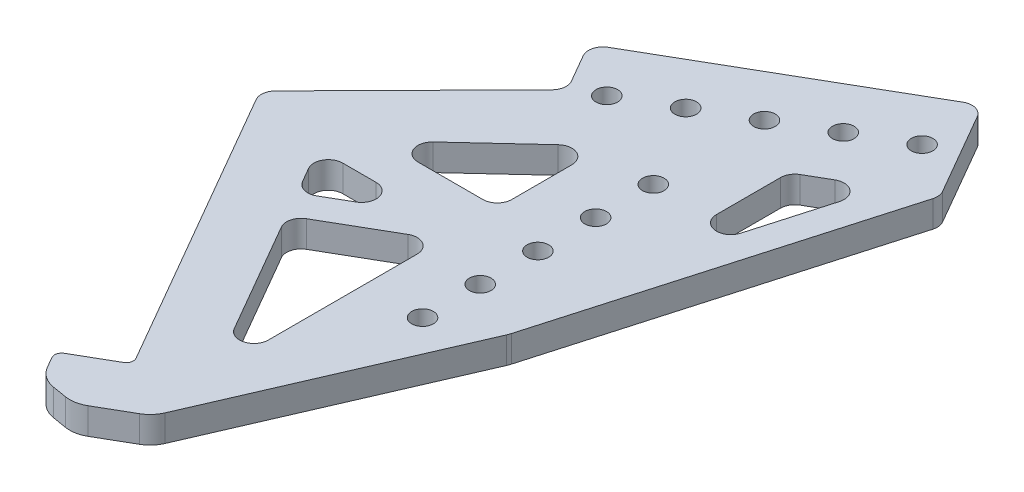
SolidWorks part; units mm, degrees
ref_plane "Front Plane" through (0, 0, 0) normal (0, 0, 1) x (1, 0, 0)
ref_plane "Top Plane" through (0, 0, 0) normal (0, 1, 0) x (1, 0, 0)
ref_plane "Right Plane" through (0, 0, 0) normal (1, 0, 0) x (0, 0, -1)
sketch "Sketch1" plane through (0, 0, 0) normal (0, 1, 0) x (1, 0, 0)
  line L0 (0, 0) -> (0, -101.6) construction
  line L1 (27.4963, 15.875) -> (-27.4963, -15.875) construction
  line L2 (25.9313, 0.3067) -> (12.7, -7.3323)
  line L3 (-11.0124, -123.6756) -> (12.6999, -68.9194)
  line L4 (-27.4963, -15.875) -> (-61.0935, -49.937)
  line L5 (25.9313, 0.3067) -> (12.7, -45.8676)
  line L6 (12.7, -45.8676) -> (12.7, -16.2776)
  line L7 (33.8463, 4.8765) -> (21.1463, 26.8735)
  line L8 (-27.4963, -15.875) -> (-33.8463, -4.8765)
  line L9 (21.1463, 26.8735) -> (-33.8463, -4.8765)
  line L10 (33.8463, 4.8765) -> (-33.8463, -4.8765) construction
  line L11 (-21.1463, -26.8735) -> (21.1463, 26.8735) construction
  line L12 (33.8463, 4.8765) -> (12.6999, -68.9194)
  line L13 (-21.1463, -26.8735) -> (-54.4806, -46.1191) construction
  line L14 (12.7, -16.2776) -> (12.7, -7.3323)
  line L15 (-61.0935, -49.937) -> (-22.9935, -115.9282)
  line L16 (-43.745, -54.5856) -> (-37.5712, -65.2788)
  line L17 (-22.9935, -115.9282) -> (-33.992, -122.2782)
  line L18 (-33.992, -122.2782) -> (-30.3258, -128.6282)
  line L19 (-30.3258, -128.6282) -> (-22.0109, -130.0256)
  line L20 (-12.7, -22.4275) -> (-12.7, -46.1065)
  line L21 (-11.0124, -123.6756) -> (-22.0109, -130.0256)
  line L22 (-42.0435, -82.9326) -> (-31.045, -76.5826) construction
  line L23 (-12.7, -54.5856) -> (-35.9837, -68.0284) construction
  line L24 (-19.05, -54.5856) -> (-43.745, -54.5856)
  line L25 (-38.2672, -46.1065) -> (-18.345, -46.1065)
  line L27 (-18.345, -27.6556) -> (-12.7, -22.4275)
  line L28 (-43.745, -54.5856) -> (-43.745, -46.1065) construction
  line L29 (-12.7, 0) -> (-12.7, -46.1065) construction
  line L30 (33.8463, 4.8765) -> (-21.1463, -26.8735) construction
  line L31 (-38.2672, -46.1065) -> (-18.345, -27.6556)
  line L32 (-18.345, -46.1065) -> (-12.7, -46.1065)
  line L33 (-18.345, -98.5797) -> (-12.7, -108.357)
  line L34 (-12.7, -101.6) -> (-12.7, -108.357)
  line L35 (-12.7, -58.2517) -> (-12.7, -101.6)
  line L36 (-12.7, -54.5856) -> (-12.7, -101.6) construction
  line L37 (-19.05, -54.5856) -> (-37.5712, -65.2788)
  line L38 (-12.7, 0) -> (-12.7, -101.6) construction
  line L39 (-12.7, -58.2517) -> (-34.3962, -70.7781)
  line L40 (-34.3962, -70.7781) -> (-18.345, -98.5797)
  line L42 (-14.2875, -51.8359) -> (-37.5712, -65.2788) construction
  circle A0 centre (21.997, 12.7) radius 2.3813
  circle A1 centre (10.9985, 6.35) radius 2.3813
  circle A2 centre (0, 0) radius 2.3813
  circle A3 centre (-10.9985, -6.35) radius 2.3813
  circle A4 centre (-21.997, -12.7) radius 2.3813
  circle A5 centre (0, -24.4695) radius 2.3813
  circle A6 centre (0, -37.1695) radius 2.3812
  circle A7 centre (0, -49.8695) radius 2.3812
  circle A8 centre (0, -62.5695) radius 2.3813
  circle A9 centre (0, -75.2695) radius 2.3813
  point P27 (0, -68.9195)
  point P28 (27.742, 6.6257)
  point P29 (6.5957, -67.1703)
  point P40 (-12.7, 0)
  point P53 (-12.7, -21.997)
  dimension "D4" = 4.7625
  dimension "D7" = 4.7625
  dimension "D1" = 60
  dimension "D2" = 63.5
  dimension "D3" = 101.6
  dimension "D5" = 6.35
  dimension "D8" = 24.4695
  dimension "D10" = 12.7
  dimension "D11" = 6.35
  dimension "D12" = 25.4
  dimension "D13" = 50.8
  dimension "D14" = 76.2
  dimension "D15" = 12.7
  dimension "D16" = 6.35
  dimension "D17" = 12.7
  dimension "D18" = 12.7
  dimension "D19" = 55.88
  dimension "D20" = 2
  dimension "D21" = 3.175
  dimension "D6" = 5
  dimension "D9" = 4
extrude "Boss-Extrude1" add sketch "Sketch1" along normal blind 5.842
fillet "Fillet1" radius 3.175 12 edges at (-43.745, 2.921, 54.5856) (25.9313, 2.921, -0.3067) (12.7, 2.921, 7.3323) (12.7, 2.921, 45.8676) (-38.2672, 2.921, 46.1065) (-12.7, 2.921, 46.1065) (-12.7, 2.921, 22.4275) (-12.7, 2.921, 108.357) (-12.7, 2.921, 58.2517) (-34.3962, 2.921, 70.7781) (-37.5712, 2.921, 65.2788) (-19.05, 2.921, 54.5856)
fillet "Fillet2" radius 3.175 5 edges at (33.8463, 2.921, -4.8765) (21.1463, 2.921, -26.8735) (-33.8463, 2.921, 4.8765) (-27.4963, 2.921, 15.875) (-61.0935, 2.921, 49.937)
fillet "Fillet3" radius 1.5875 2 edges at (-33.992, 2.921, 122.2782) (-22.9935, 2.921, 115.9282)
fillet "Fillet5" radius 6.35 4 edges at (-30.3258, 2.921, 128.6282) (-22.0109, 2.921, 130.0256) (12.6999, 2.921, 68.9194) (-11.0124, 2.921, 123.6756)
